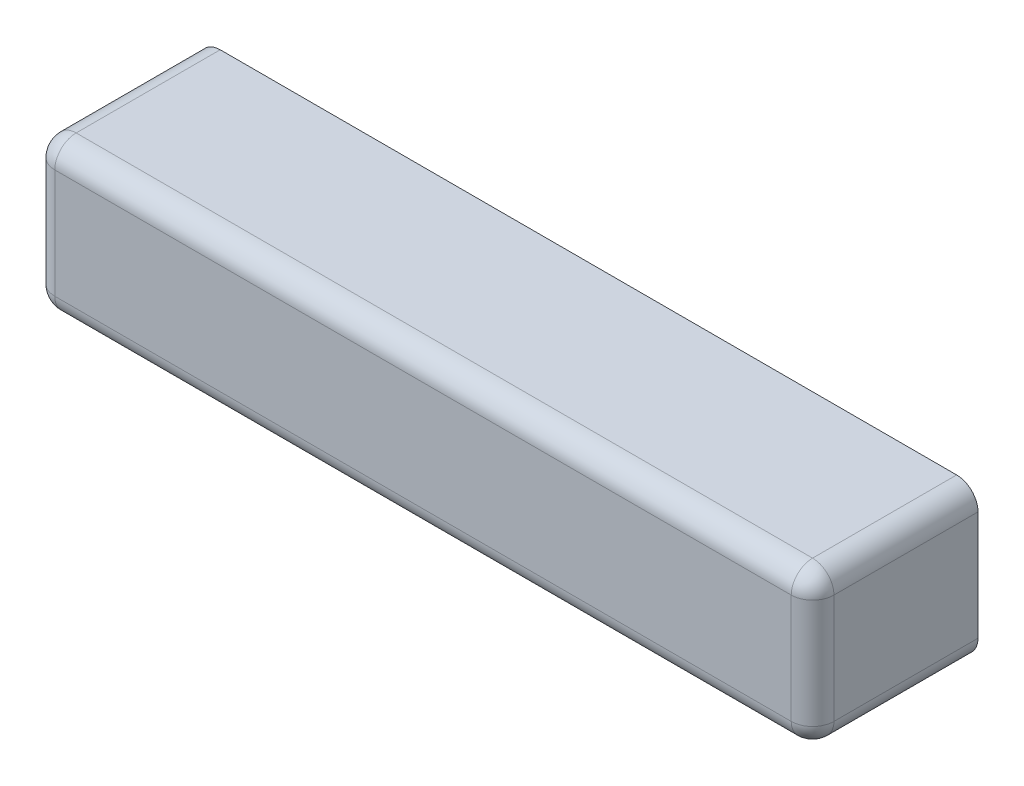
SolidWorks part; units mm, degrees
ref_plane "Front Plane" through (0, 0, 0) normal (0, 0, 1) x (1, 0, 0)
ref_plane "Top Plane" through (0, 0, 0) normal (0, 1, 0) x (1, 0, 0)
ref_plane "Right Plane" through (0, 0, 0) normal (1, 0, 0) x (0, 0, -1)
sketch "Sketch1" plane through (0, 0, 0) normal (0, 0, 1) x (1, 0, 0)
  line L1 (0, 0) -> (29.2, 0)
  line L2 (0, 0) -> (0, 5.7)
  line L3 (0, 5.7) -> (29.2, 5.7)
  line L4 (29.2, 0) -> (29.2, 5.7)
  dimension "D1" = 29.2
  dimension "D2" = 5.7
extrude "Boss-Extrude1" add sketch "Sketch1" along normal blind 6.2
fillet "Fillet1" radius 0.8 8 edges at (14.6, 5.7, 6.2) (29.2, 2.85, 6.2) (14.6, 0, 6.2) (0, 2.85, 6.2) (29.2, 5.7, 3.1) (29.2, 0, 3.1) (0, 0, 3.1) (0, 5.7, 3.1)
